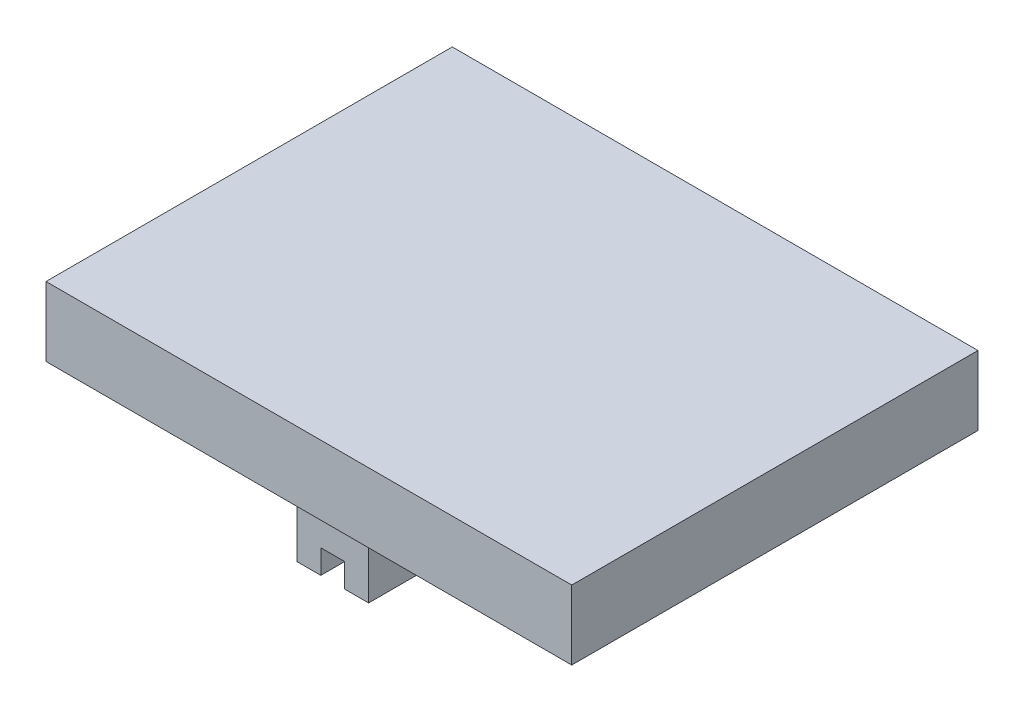
SolidWorks part; units mm, degrees
ref_plane "Front Plane" through (0, 0, 0) normal (0, 0, 1) x (1, 0, 0)
ref_plane "Top Plane" through (0, 0, 0) normal (0, 1, 0) x (1, 0, 0)
ref_plane "Right Plane" through (0, 0, 0) normal (1, 0, 0) x (0, 0, -1)
sketch "Sketch1" plane through (0, 0, 0) normal (0, 0, 1) x (1, 0, 0)
  line L0 (0, 0) -> (1, 0)
  line L1 (1, 0) -> (1, 1)
  line L2 (1, 1) -> (2, 1)
  line L3 (2, 1) -> (2, 0)
  line L4 (2, 0) -> (3, 0)
  line L5 (3, 0) -> (3, 3)
  line L6 (3, 3) -> (0, 3)
  line L7 (0, 3) -> (0, 0)
  dimension "D1" = 3
  dimension "D2" = 3
  dimension "D3" = 1
extrude "Boss-Extrude1" add sketch "Sketch1" along normal blind 15
sketch "Sketch2" plane through (0, 3, 0) normal (0, 1, 0) x (1, 0, 0)
  line L0 (0, -15) -> (0, 0) construction
  line L1 (-9.5, 1) -> (12.5, 1)
  line L2 (-9.5, 1) -> (-9.5, -16)
  line L3 (-9.5, -16) -> (12.5, -16)
  line L4 (12.5, 1) -> (12.5, -16)
  line L5 (3, 0) -> (0, 0) construction
  point P4 (0, -7.5)
  point P7 (-9.5, -7.5)
  point P10 (1.5, 0)
  point P11 (1.5, 1)
  dimension "D1" = 17
  dimension "D2" = 22
extrude "Boss-Extrude2" add sketch "Sketch2" along normal blind 2.9
